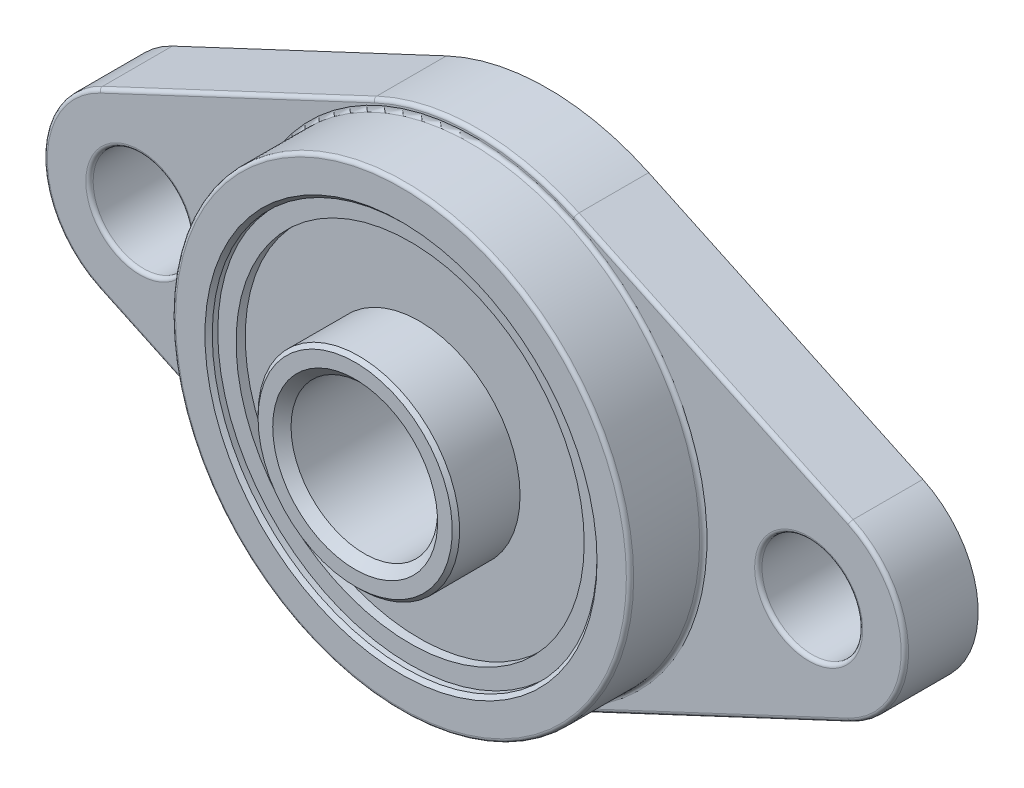
SolidWorks part; units mm, degrees
ref_plane "正面" through (0, 0, 0) normal (0, 0, 1) x (1, 0, 0)
ref_plane "平面" through (0, 0, 0) normal (0, 1, 0) x (1, 0, 0)
ref_plane "右側面" through (0, 0, 0) normal (1, 0, 0) x (0, 0, -1)
sketch "Sketch1" plane through (0, 0, 0) normal (0, 0, 1) x (1, 0, 0)
  circle A0 centre (0, 0) radius 10.5
  dimension "D1" = 21
extrude "Boss-Extrude1" add sketch "Sketch1" along normal blind 7
sketch "Sketch2" plane through (0, 0, 0) normal (0, 0, -1) x (-1, 0, 0)
  circle A0 centre (0, 0) radius 9.5
  circle A1 centre (0, 0) radius 5.5
  dimension "D1" = 19
  dimension "D2" = 11
extrude "Cut-Extrude1" cut sketch "Sketch2" against normal blind 0.5
sketch "Sketch3" plane through (0, 0, 0) normal (0, 0, -1) x (-1, 0, 0)
  circle A0 centre (0, 0) radius 5.5
extrude "Boss-Extrude2" add sketch "Sketch3" against normal blind 10
sketch "Sketch4" plane through (0, 0, 0) normal (0, 0, -1) x (-1, 0, 0)
  circle A0 centre (0, 0) radius 4
  dimension "D1" = 8
extrude "Cut-Extrude2" cut sketch "Sketch4" against normal up to next
sketch "Sketch5" plane through (0, 0, 7) normal (0, 0, 1) x (1, 0, 0)
  circle A0 centre (0, 0) radius 9.5
  circle A1 centre (0, 0) radius 5.5
  dimension "D1" = 19
extrude "Cut-Extrude3" cut sketch "Sketch5" against normal blind 0.5
chamfer "Chamfer1" distance 0.5 angle 45 1 edges at (-4, 0, 10)
chamfer "Chamfer2" distance 0.2 angle 45 1 edges at (-5.5, 0, 10)
sketch "Sketch6" plane through (0, 0, 0.5) normal (0, 0, -1) x (-1, 0, 0)
  line L0 (0, 13) -> (0, -13) construction
  line L1 (-23.5, 0) -> (18.5, 0) construction
  line L2 (-20.4795, 4.7531) -> (-5.5205, 11.7696)
  line L3 (-20.4795, -4.7531) -> (-5.5205, -11.7696)
  line L4 (20.4795, -4.7531) -> (5.5205, -11.7696)
  line L5 (20.4795, 4.7531) -> (5.5205, 11.7696)
  arc A0 (-20.4795, 4.7531) -> (-20.4795, -4.7531) centre (-18.25, 0) ccw
  circle A1 centre (-18.25, 0) radius 2.75
  circle A2 centre (0, 0) radius 13 construction
  circle A3 centre (-18.25, 0) radius 5.25 construction
  arc A4 (20.4795, 4.7531) -> (20.4795, -4.7531) centre (18.25, 0) cw
  circle A5 centre (18.25, 0) radius 2.75
  arc A6 (-5.5205, 11.7696) -> (6.4951, 11.2612) centre (0, 0) cw
  arc A7 (-5.5205, -11.7696) -> (6.4951, -11.2612) centre (0, 0) ccw
  circle A8 centre (0, 0) radius 10.5
  point P2 (0, 0)
  dimension "D3" = 5.5
  dimension "D6" = 26
  dimension "D1" = 26
  dimension "D2" = 42
  dimension "D4" = 5.25
  dimension "D5" = 23.5
extrude "Boss-Extrude3" add sketch "Sketch6" against normal blind 4 from offset 1
sketch "Sketch7" plane through (0, 0, -0.5) normal (0, 0, -1) x (-1, 0, 0)
  line L0 (0, 13) -> (0, -13) construction
  line L1 (-23.5, 0) -> (23.5, 0) construction
  line L2 (-22.2604, 1.4069) -> (-5.2959, 10.208)
  line L3 (-22.2604, -1.4069) -> (-5.2959, -10.208)
  line L4 (22.2604, -1.4069) -> (5.2959, -10.208)
  line L5 (22.2604, 1.4069) -> (5.2959, 10.208)
  arc A0 (5.5205, 11.7696) -> (-5.5205, 11.7696) centre (0, 0) ccw construction
  arc A1 (-5.5205, -11.7696) -> (5.5205, -11.7696) centre (0, 0) ccw construction
  arc A2 (-20.4795, 4.7531) -> (-20.4795, -4.7531) centre (-18.25, 0) ccw construction
  arc A3 (20.4795, -4.7531) -> (20.4795, 4.7531) centre (18.25, 0) ccw construction
  circle A4 centre (18.25, 0) radius 2.75 construction
  circle A5 centre (-18.25, 0) radius 2.75 construction
  circle A6 centre (18.25, 0) radius 2.75 construction
  circle A7 centre (-18.25, 0) radius 2.75 construction
  circle A8 centre (-18.25, 0) radius 4.25 construction
  circle A9 centre (0, 0) radius 11.5 construction
  arc A10 (-22.2604, 1.4069) -> (-22.2604, -1.4069) centre (-18.25, 0) cw
  arc A11 (-5.2959, 10.208) -> (5.3348, 10.1877) centre (0, 0) cw
  arc A12 (-5.2959, -10.208) -> (5.3348, -10.1877) centre (0, 0) ccw
  arc A13 (22.2604, 1.4069) -> (22.2604, -1.4069) centre (18.25, 0) ccw
  dimension "D1" = 8.5
  dimension "D2" = 23
extrude "Cut-Extrude4" cut sketch "Sketch7" against normal blind 0.4 and the other way through all
fillet "Fillet1" radius 1 4 edges at (17.0908, -4.0889, -0.3) (17.0908, 4.0889, -0.3) (-17.0908, -4.0889, -0.3) (-17.0908, 4.0889, -0.3)
sketch "Sketch8" plane through (0, 0, 3.5) normal (0, 0, 1) x (1, 0, 0)
  circle A0 centre (0, 0) radius 12.5
  circle A1 centre (0, 0) radius 10.5 construction
  circle A2 centre (0, 0) radius 10.5
  dimension "D1" = 25
extrude "Boss-Extrude4" add sketch "Sketch8" along normal blind 4
fillet "Fillet2" radius 0.2 1 edges at (12.5, 0, 7.5)
fillet "Fillet3" radius 0.2 11 edges at (-12.5, 0, 3.5) (-21, 0, 3.5) (15.5, 0, 3.5) (0, -13, 3.5) (-13, -8.2614, 3.5) (-23.5, 0, 3.5) (-13, 8.2614, 3.5) (0, 13, 3.5) (13, 8.2614, 3.5) (23.5, 0, 3.5) (13, -8.2614, 3.5)
chamfer "Chamfer3" distance 0.2 angle 45 1 edges at (10.5, 0, 7.5)
